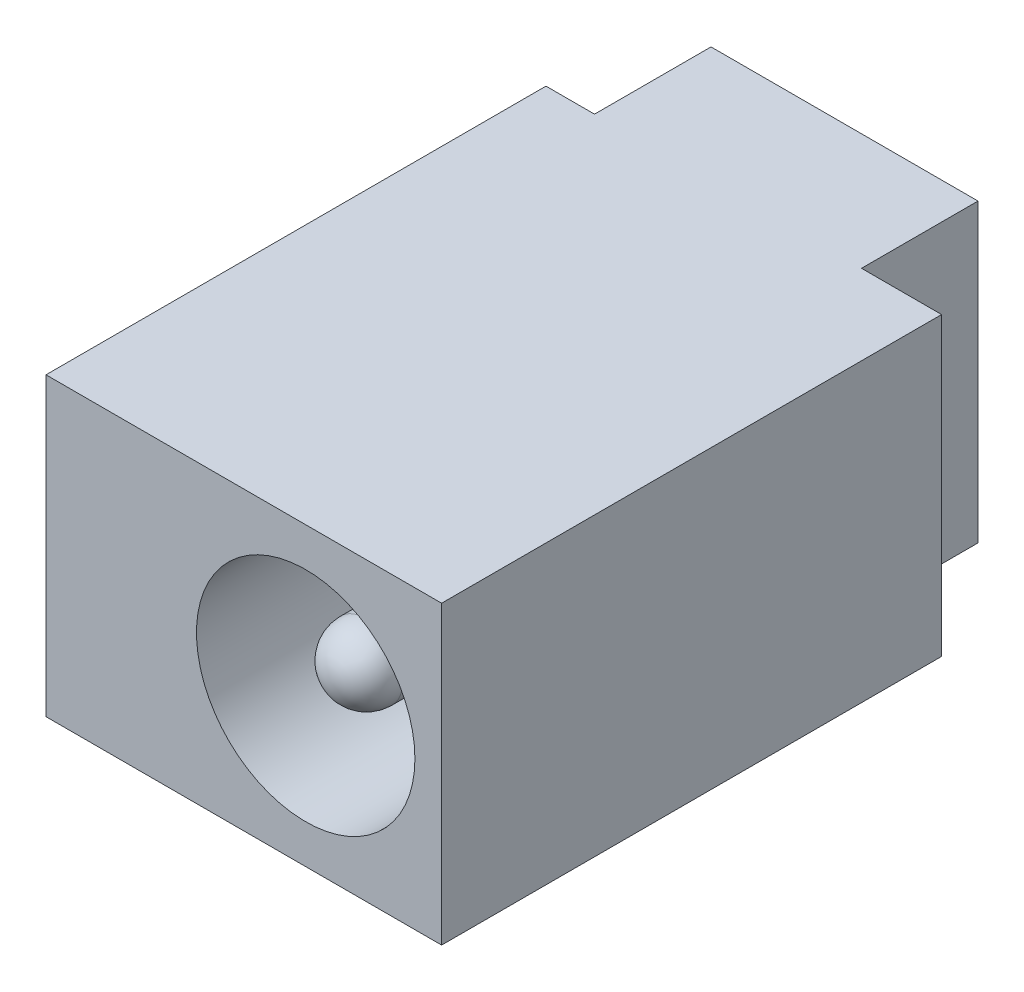
SolidWorks part; units mm, degrees
ref_plane "Спереди" through (0, 0, 0) normal (0, 0, 1) x (1, 0, 0)
ref_plane "Сверху" through (0, 0, 0) normal (0, 1, 0) x (1, 0, 0)
ref_plane "Справа" through (0, 0, 0) normal (1, 0, 0) x (0, 0, -1)
sketch "Эскиз1" plane through (0, 0, 0) normal (0, 1, 0) x (1, 0, 0)
  line L0 (-4.075, 3.95) -> (-3.075, 3.95)
  line L1 (4.075, -6.35) -> (-4.075, -6.35)
  line L2 (4.075, -6.35) -> (4.075, 3.95)
  line L3 (2.425, 6.35) -> (-3.075, 6.35)
  line L4 (-4.075, -6.35) -> (-4.075, 3.95)
  line L5 (4.075, -6.35) -> (-4.075, 6.35) construction
  line L6 (4.075, 6.35) -> (-4.075, -6.35) construction
  line L7 (-3.075, 3.95) -> (-3.075, 6.35)
  line L8 (2.425, 6.35) -> (2.425, 3.95)
  line L9 (2.425, 3.95) -> (4.075, 3.95)
  point P0 (0, 0)
  point P11 (0, 0)
  dimension "D1" = 8.15
  dimension "D2" = 12.7
  dimension "D3" = 2.4
  dimension "D4" = 5.5
  dimension "D5" = 1
extrude "Бобышка-Вытянуть1" add sketch "Эскиз1" along normal blind 6.1
sketch "Эскиз2" plane through (0, 0, 6.35) normal (0, 0, 1) x (1, 0, 0)
  line L0 (4.075, 3.05) -> (-4.075, 3.05) construction
  line L1 (4.075, 6.1) -> (4.075, 0) construction
  line L2 (-4.075, 6.1) -> (-4.075, 0) construction
  circle A0 centre (1.275, 3.05) radius 2.25
  dimension "D1" = 4.5
  dimension "D2" = 2.8
extrude "Вырез-Вытянуть1" cut sketch "Эскиз2" against normal blind 8
sketch "Эскиз3" plane through (0, 0, -1.65) normal (0, 0, 1) x (1, 0, 0)
  circle A0 centre (1.275, 3.05) radius 0.75
  dimension "D1" = 1.5
extrude "Бобышка-Вытянуть2" add sketch "Эскиз3" along normal blind 7.5
fillet "Скругление1" radius 0.75 1 edges at (2.025, 3.05, 5.85)
